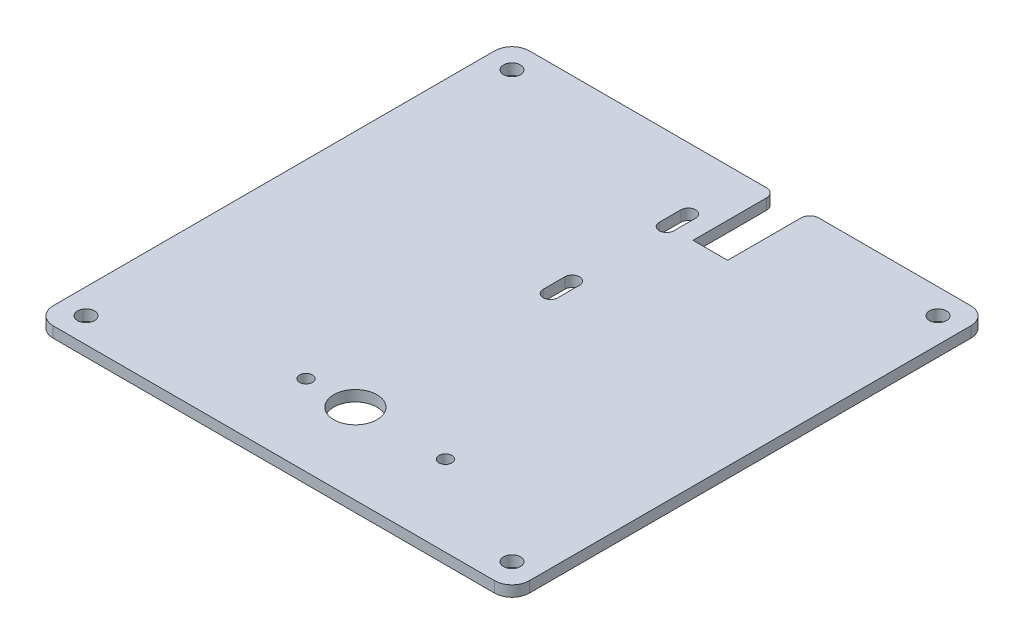
SolidWorks part; units mm, degrees
ref_plane "Front Plane" through (0, 0, 0) normal (0, 0, 1) x (1, 0, 0)
ref_plane "Top Plane" through (0, 0, 0) normal (0, 1, 0) x (1, 0, 0)
ref_plane "Right Plane" through (0, 0, 0) normal (1, 0, 0) x (0, 0, -1)
sketch "Sketch1" plane through (0, 0, 0) normal (0, 1, 0) x (1, 0, 0)
  line L5 (-69.85, -69.85) -> (69.85, -69.85)
  line L6 (-69.85, -69.85) -> (-69.85, 69.85)
  line L7 (-69.85, 69.85) -> (69.85, 69.85)
  line L8 (69.85, -69.85) -> (69.85, 69.85)
  line L9 (-69.85, -69.85) -> (69.85, 69.85) construction
  line L10 (-69.85, 69.85) -> (69.85, -69.85) construction
  line L11 (-69.85, 69.85) -> (69.85, 69.85)
  circle A0 centre (62.484, -62.484) radius 2.4892
  circle A1 centre (62.484, -62.484) radius 7.366 construction
  circle A8 centre (-62.484, 62.484) radius 2.4892
  circle A9 centre (-62.484, 62.484) radius 7.366 construction
  circle A10 centre (62.484, 62.484) radius 2.4892
  circle A11 centre (62.484, 62.484) radius 7.366 construction
  circle A12 centre (-62.484, -62.484) radius 2.4892
  circle A13 centre (-62.484, -62.484) radius 7.366 construction
  dimension "D3" = 14.732
  dimension "D4" = 4.9784
  dimension "D13" = 4.9784
  dimension "D14" = 14.732
  dimension "D15" = 4.9784
  dimension "D16" = 14.732
  dimension "D17" = 4.9784
  dimension "D18" = 14.732
  dimension "D11" = 139.7
  dimension "D12" = 139.7
extrude "Boss-Extrude1" add sketch "Sketch1" along normal blind 3.175
sketch "Sketch2" plane through (0, 3.175, 0) normal (0, 1, 0) x (1, 0, 0)
  line L0 (0, 123.83) -> (0, 28.326) construction
  line L1 (-69.85, 69.85) -> (69.85, 69.85)
  line L2 (-69.85, 69.85) -> (-69.85, 123.83) construction
  line L3 (-69.85, 123.83) -> (69.85, 123.83) construction
  line L4 (69.85, 69.85) -> (69.85, 123.83) construction
  line L5 (0, 11.308) -> (0, 45.344) construction
  line L6 (0, 45.344) -> (0, 51.694) construction
  line L7 (-2.1527, 45.344) -> (-2.1527, 51.694)
  line L8 (2.1527, 45.344) -> (2.1527, 51.694)
  line L9 (0, 11.308) -> (0, 17.658) construction
  line L10 (-2.1526, 11.308) -> (-2.1526, 17.658)
  line L11 (2.1527, 11.308) -> (2.1527, 17.658)
  line L12 (17.5427, 69.85) -> (7.3827, 69.85)
  line L13 (7.3827, 69.85) -> (17.5427, 69.85)
  line L14 (7.3827, 69.85) -> (7.3827, 45.72)
  line L15 (7.3827, 45.72) -> (17.5427, 45.72)
  line L16 (17.5427, 69.85) -> (17.5427, 45.72)
  arc A0 (-2.1527, 45.344) -> (2.1527, 45.344) centre (0, 45.344) ccw
  arc A1 (2.1527, 51.694) -> (-2.1527, 51.694) centre (0, 51.694) ccw
  arc A2 (-2.1526, 11.308) -> (2.1527, 11.308) centre (0, 11.308) ccw
  arc A3 (2.1527, 17.658) -> (-2.1526, 17.658) centre (0, 17.658) ccw
  point P10 (0, 48.519)
  point P16 (0, 14.483)
  dimension "D6" = 4.3053
  dimension "D7" = 4.3053
  dimension "D1" = 95.504
  dimension "D2" = 53.98
  dimension "D3" = 34.036
  dimension "D4" = 6.35
  dimension "D5" = 6.35
  dimension "D8" = 5.23
  dimension "D9" = 10.16
  dimension "D10" = 24.13
extrude "Cut-Extrude2" cut sketch "Sketch2" against normal up to surface (3.175 mm away) contours L16 L1 L14 L15 | A0 L8 A1 L7 | A3 L10 A2 L11 up to face at (-62.484, 0, 64.9732)
sketch "Sketch3" plane through (0, 3.175, 0) normal (0, 1, 0) x (1, 0, 0)
  line L0 (69.85, -69.85) -> (69.85, 69.85) construction
  line L1 (-69.85, -69.85) -> (69.85, -69.85) construction
  line L2 (-69.85, -69.85) -> (-69.85, -46.1981) construction
  line L3 (-69.85, -46.1981) -> (69.85, -46.1981) construction
  line L4 (69.85, -69.85) -> (69.85, -46.1981) construction
  circle A0 centre (-14.224, -46.1981) radius 1.905
  circle A1 centre (26.67, -46.1981) radius 1.905
  circle A2 centre (0.254, -46.1981) radius 6.35
  dimension "D4" = 3.81
  dimension "D5" = 3.81
  dimension "D6" = 12.7
  dimension "D1" = 23.6519
  dimension "D2" = 40.894
  dimension "D3" = 14.478
  dimension "D7" = 43.18
extrude "Cut-Extrude4" cut sketch "Sketch3" against normal up to surface (3.175 mm away) contours A2 | A1 | A0 up to face at (0, 0, -48.519)
fillet "Fillet2" radius 5.08 1 edges at (-69.85, 1.5875, 69.85)
fillet "Fillet3" radius 5.08 1 edges at (69.85, 1.5875, 69.85)
fillet "Fillet4" radius 5.08 1 edges at (69.85, 1.5875, -69.85)
fillet "Fillet5" radius 5.08 1 edges at (-69.85, 1.5875, -69.85)
fillet "Fillet6" radius 2.54 1 edges at (7.3827, 1.5875, -69.85)
fillet "Fillet8" radius 2.54 1 edges at (17.5427, 1.5875, -69.85)
